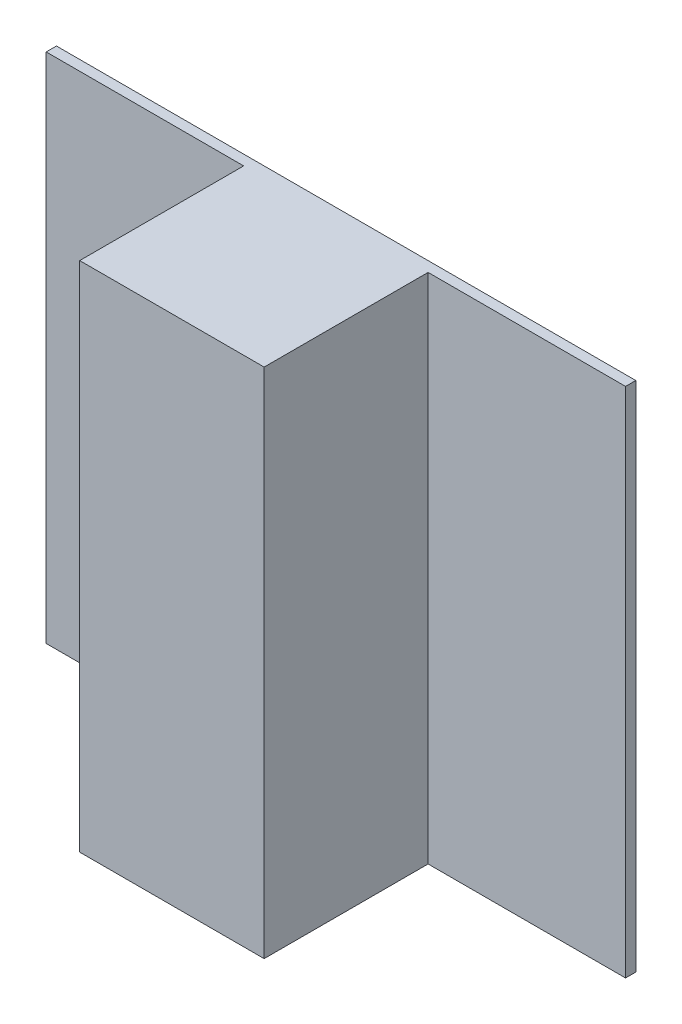
SolidWorks part; units mm, degrees
ref_plane "Plan de face" through (0, 0, 0) normal (0, 0, 1) x (1, 0, 0)
ref_plane "Plan de dessus" through (0, 0, 0) normal (0, 1, 0) x (1, 0, 0)
ref_plane "Plan de droite" through (0, 0, 0) normal (1, 0, 0) x (0, 0, -1)
sketch "Esquisse1" plane through (0, 0, 0) normal (0, 0, 1) x (1, 0, 0)
  line L1 (0, 0) -> (-90, 0)
  line L2 (0, 0) -> (0, 250)
  line L3 (0, 250) -> (-90, 250)
  line L4 (-90, 0) -> (-90, 250)
  dimension "D1" = 250
  dimension "D2" = 90
extrude "Boss.-Extru.1" add sketch "Esquisse1" along normal blind 5
sketch "Esquisse2" plane through (0, 0, 0) normal (0, 0, -1) x (-1, 0, 0)
  line L0 (5, 245) -> (5, 5)
  line L1 (0, 250) -> (90, 250)
  line L2 (0, 250) -> (0, 0)
  line L3 (0, 0) -> (90, 0)
  line L4 (90, 250) -> (90, 0)
  line L5 (5, 5) -> (85, 5)
  line L6 (85, 245) -> (85, 5)
  line L7 (5, 245) -> (85, 245)
  dimension "D1" = 5
extrude "Boss.-Extru.2" add sketch "Esquisse2" along normal blind 75
sketch "Esquisse3" plane through (0, 0, -75) normal (0, 0, -1) x (-1, 0, 0)
  line L0 (90, 250) -> (0, 250) construction
  line L1 (6.0255, 250) -> (-96.3477, 250)
  line L2 (5, 245) -> (5, 5)
  line L3 (-31.3477, 0) -> (-96.3477, 0)
  line L4 (-96.3477, 250) -> (-96.3477, 0)
  line L5 (85, 245) -> (5, 245) construction
  line L6 (45, 245) -> (5, 245)
  line L7 (45, 245) -> (45, 250)
  line L8 (45, 250) -> (6.0255, 250)
  line L9 (5, 245) -> (5, 5) construction
  line L10 (5, 5) -> (85, 5) construction
  line L11 (45, 5) -> (5, 5)
  line L12 (45, 5) -> (45, 0)
  line L13 (45, 0) -> (-31.3477, 0)
  dimension "D1" = 65
extrude "Boss.-Extru.3" add sketch "Esquisse3" along normal blind 5
mirror "Symétrie1" about plane through (-45, 245, -80) normal (1, 0, 0) of "Boss.-Extru.3"
